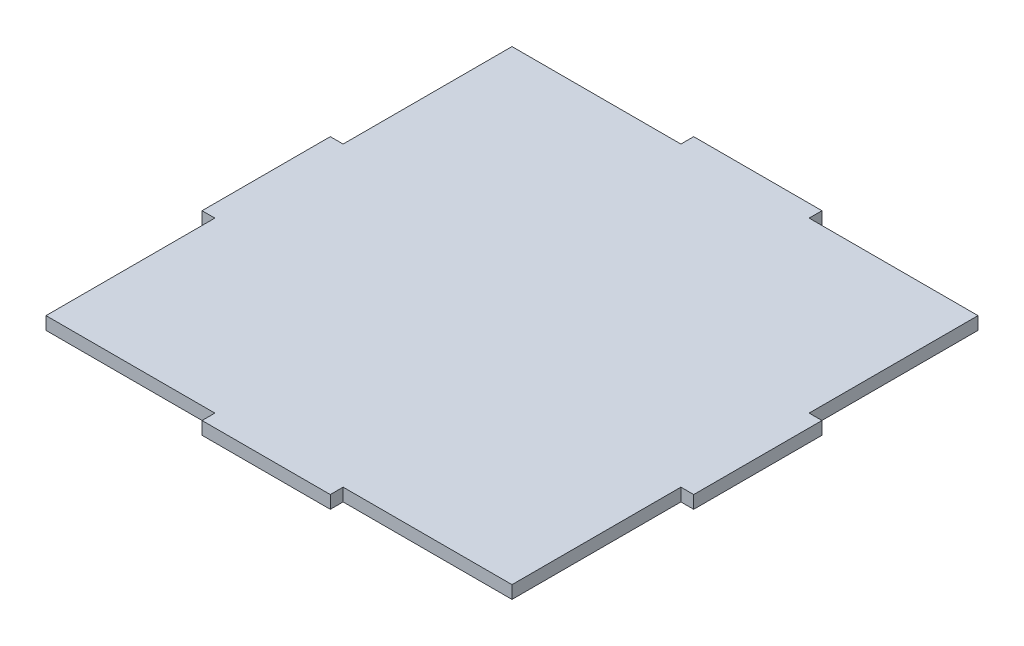
SolidWorks part; units mm, degrees
ref_plane "Front Plane" through (0, 0, 0) normal (0, 0, 1) x (1, 0, 0)
ref_plane "Top Plane" through (0, 0, 0) normal (0, 1, 0) x (1, 0, 0)
ref_plane "Right Plane" through (0, 0, 0) normal (1, 0, 0) x (0, 0, -1)
sketch "Sketch1" plane through (0, 0, 0) normal (0, 1, 0) x (1, 0, 0)
  line L0 (-57.5, 15) -> (-54.5, 15)
  line L1 (57.5, 57.5) -> (-57.5, 57.5)
  line L2 (57.5, 57.5) -> (57.5, -57.5)
  line L3 (57.5, -57.5) -> (-57.5, -57.5)
  line L4 (-57.5, 57.5) -> (-57.5, -57.5)
  line L5 (57.5, 57.5) -> (-57.5, -57.5) construction
  line L6 (57.5, -57.5) -> (-57.5, 57.5) construction
  line L7 (-54.5, 15) -> (-54.5, -15)
  line L8 (-54.5, -15) -> (-57.5, -15)
  line L9 (-15, 57.5) -> (-15, 54.5)
  line L10 (-15, 54.5) -> (15, 54.5)
  line L11 (15, 54.5) -> (15, 57.5)
  line L12 (57.5, 15) -> (54.5, 15)
  line L13 (54.5, 15) -> (54.5, -15)
  line L14 (54.5, -15) -> (57.5, -15)
  line L15 (-15, -57.5) -> (-15, -54.5)
  line L16 (-15, -54.5) -> (15, -54.5)
  line L17 (15, -54.5) -> (15, -57.5)
  line L18 (0, 57.5) -> (0, -57.5) construction
  line L19 (-57.5, 0) -> (57.5, 0) construction
  line L20 (0.2252, 54.5727) -> (0.2252, -60.4273) construction
  line L21 (-54.5, 15) -> (-54.5, 54.5)
  line L22 (-54.5, 54.5) -> (-15, 54.5)
  line L23 (15, 54.5) -> (54.5, 54.5)
  line L24 (54.5, 54.5) -> (54.5, 15)
  line L25 (54.5, -15) -> (54.5, -54.5)
  line L26 (54.5, -54.5) -> (15, -54.5)
  line L27 (-15, -54.5) -> (-54.5, -54.5)
  line L28 (-54.5, -54.5) -> (-54.5, -15)
  point P0 (0, 0)
  dimension "D1" = 115
  dimension "D2" = 115
  dimension "D3" = 3
  dimension "D4" = 30
extrude "Boss-Extrude1" add sketch "Sketch1" along normal blind 3 contours L17 L16 L15 L3 | L8 L7 L0 L4 | L10 L11 L1 L9 | L28 L27 L16 L26 L25 L13 L24 L23 L10 L22 L21 L7 | L13 L14 L2 L12
